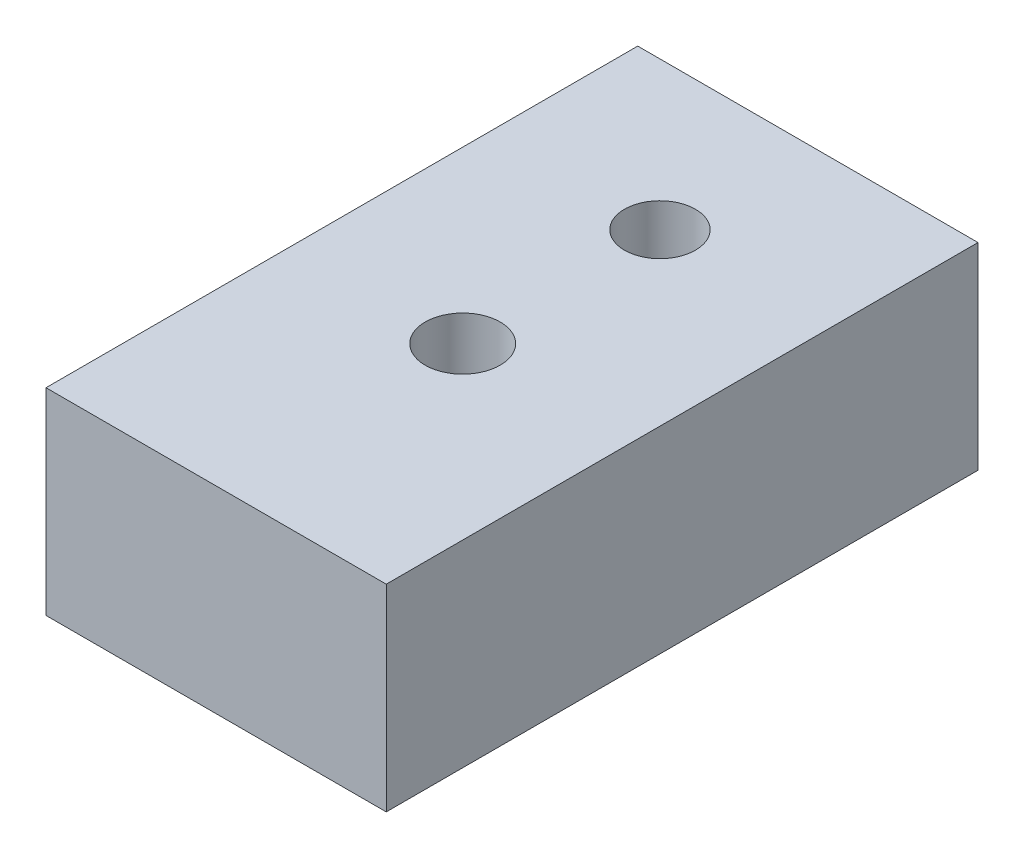
SolidWorks part; units mm, degrees
ref_plane "Front Plane" through (0, 0, 0) normal (0, 0, 1) x (1, 0, 0)
ref_plane "Top Plane" through (0, 0, 0) normal (0, 1, 0) x (1, 0, 0)
ref_plane "Right Plane" through (0, 0, 0) normal (1, 0, 0) x (0, 0, -1)
sketch "Sketch1" plane through (0, 0, 0) normal (0, 1, 0) x (1, 0, 0)
  line L1 (-10.9538, 19.05) -> (10.9537, 19.05)
  line L2 (-10.9538, 19.05) -> (-10.9537, -19.05)
  line L3 (-10.9537, -19.05) -> (10.9538, -19.05)
  line L4 (10.9537, 19.05) -> (10.9538, -19.05)
  line L5 (-10.9538, 19.05) -> (10.9538, -19.05) construction
  line L6 (-10.9537, -19.05) -> (10.9537, 19.05) construction
  point P0 (0, 0)
  dimension "D1" = 38.1
  dimension "D2" = 21.9075
extrude "Boss-Extrude1" add sketch "Sketch1" along normal blind 12.7
sketch "Sketch2" plane through (0, 12.7, 0) normal (0, 1, 0) x (1, 0, 0)
  line L0 (10.9537, 19.05) -> (-10.9538, 19.05) construction
  circle A0 centre (0, 9.525) radius 2.286
  circle A1 centre (0, -3.175) radius 2.413
  point P7 (0, 0)
  dimension "D1" = 9.525
  dimension "D2" = 4.572
  dimension "D3" = 4.826
  dimension "D4" = 12.7
extrude "Cut-Extrude1" cut sketch "Sketch2" against normal through all
